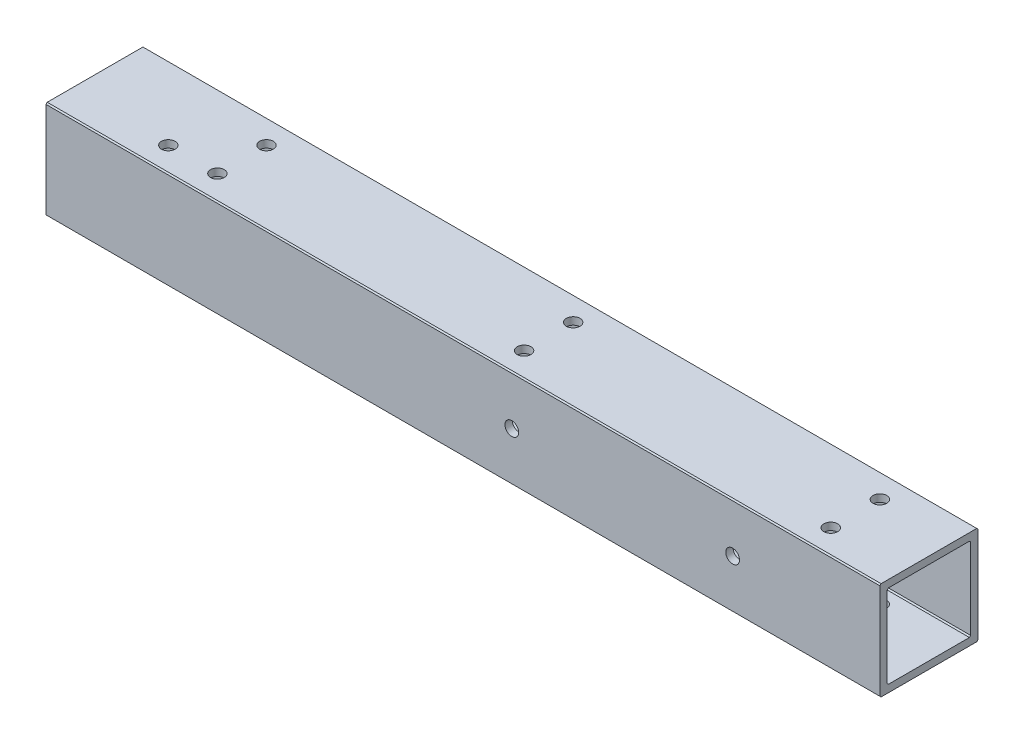
SolidWorks part; units mm, degrees
ref_plane "Front Plane" through (0, 0, 0) normal (0, 0, 1) x (1, 0, 0)
ref_plane "Top Plane" through (0, 0, 0) normal (0, 1, 0) x (1, 0, 0)
ref_plane "Right Plane" through (0, 0, 0) normal (1, 0, 0) x (0, 0, -1)
ref_plane "Plane1" through (0, -102, 0) normal (0, 1, 0) x (1, 0, 0)
sketch "Sketch1" plane through (0, -102, 0) normal (0, 1, 0) x (1, 0, 0)
  line L0 (250, -140) -> (250, -100)
  line L1 (250, -100) -> (-89.85, -100)
  line L2 (-89.85, -100) -> (-89.85, -140)
  line L3 (-89.85, -140) -> (250, -140)
extrude "Boss-Extrude1" add sketch "Sketch1" against normal blind 40
sketch "Sketch2" plane through (-89.85, 0, 0) normal (-1, 0, 0) x (0, 0, 1)
  line L0 (103, -139) -> (137, -139)
  line L1 (137, -139) -> (137, -105)
  line L2 (137, -105) -> (103, -105)
  line L3 (103, -105) -> (103, -139)
extrude "Cut-Extrude1" cut sketch "Sketch2" against normal through all
hole_wizard "Ø5.6 (5.6) Diameter Hole1" positions "Sketch4" profile "Sketch3" hole size "Ø5.6" standard "ANSI Metric"
sketch "Sketch4" plane through (0, -139, 0) normal (0, 1, 0) x (1, 0, 0)
  point P0 (220, -130)
  point P1 (95, -130)
  point P2 (220, -110)
  point P3 (95, -110)
  point P4 (-30, -130)
  point P5 (-50, -130)
  point P6 (-30, -110)
sketch "Sketch3" plane through (220, -139, 130) normal (1, 0, 0) x (0, 0, 1)
  line L0 (0, 0) -> (0, 3)
  line L1 (0, 3) -> (2.8, 3)
  line L2 (2.8, 3) -> (2.8, 0)
  line L5 (2.8, 0) -> (0, 0)
  line L11 (0, -6.35) -> (0, 107.95) construction
  dimension "Thru Hole Dia." = 5.6
  dimension "Thru Hole Depth" = 3
hole_wizard "Ø5.6 (5.6) Diameter Hole2" positions "Sketch6" profile "Sketch5" hole size "Ø5.6" standard "ANSI Metric"
sketch "Sketch6" plane through (0, 0, 100) normal (0, 0, -1) x (-1, 0, 0)
  point P0 (-190, -122)
  point P1 (-100, -122)
sketch "Sketch5" plane through (190, -122, 100) normal (1, 0, 0) x (0, 1, 0)
  line L0 (0, 0) -> (0, 3)
  line L1 (0, 3) -> (2.8, 3)
  line L2 (2.8, 3) -> (2.8, 0)
  line L5 (2.8, 0) -> (0, 0)
  line L11 (0, -6.35) -> (0, 107.95) construction
  dimension "Thru Hole Dia." = 5.6
  dimension "Thru Hole Depth" = 3
hole_wizard "Ø5.6 (5.6) Diameter Hole3" positions "Sketch8" profile "Sketch7" hole size "Ø5.6" standard "ANSI Metric"
sketch "Sketch8" plane through (0, 0, 137) normal (0, 0, -1) x (-1, 0, 0)
  point P0 (-190, -122)
  point P1 (-100, -122)
sketch "Sketch7" plane through (190, -122, 137) normal (1, 0, 0) x (0, 1, 0)
  line L0 (0, 0) -> (0, 3)
  line L1 (0, 3) -> (2.8, 3)
  line L2 (2.8, 3) -> (2.8, 0)
  line L5 (2.8, 0) -> (0, 0)
  line L11 (0, -6.35) -> (0, 107.95) construction
  dimension "Thru Hole Dia." = 5.6
  dimension "Thru Hole Depth" = 3
hole_wizard "Ø5.6 (5.6) Diameter Hole4" positions "Sketch10" profile "Sketch9" hole size "Ø5.6" standard "ANSI Metric"
sketch "Sketch10" plane through (0, -102, 0) normal (0, 1, 0) x (1, 0, 0)
  point P0 (220, -130)
  point P1 (95, -130)
  point P2 (220, -110)
  point P3 (95, -110)
  point P4 (-30, -130)
  point P5 (-50, -130)
  point P6 (-30, -110)
sketch "Sketch9" plane through (220, -102, 130) normal (1, 0, 0) x (0, 0, 1)
  line L0 (0, 0) -> (0, 40)
  line L1 (0, 40) -> (2.8, 40)
  line L2 (2.8, 40) -> (2.8, 0)
  line L5 (2.8, 0) -> (0, 0)
  line L11 (0, -6.35) -> (0, 107.95) construction
  dimension "Thru Hole Dia." = 5.6
  dimension "Thru Hole Depth" = 40
chamfer "Chamfer1" distance 0.5 angle 45 8 edges at (80.075, -142, 100) (80.075, -102, 100) (80.075, -102, 140) (80.075, -105, 137) (80.075, -142, 140) (80.075, -139, 103) (80.075, -139, 137) (80.075, -105, 103)
